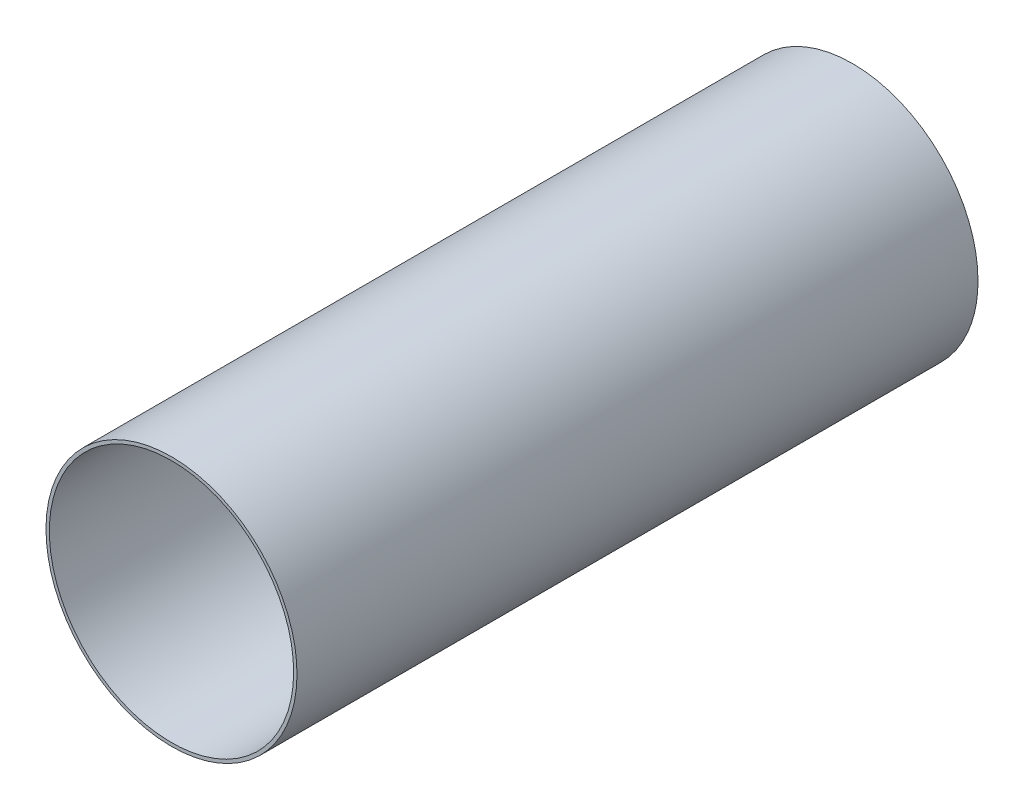
SolidWorks part; units mm, degrees
material "Thornel VCB-20 Carbon Cloth"
ref_plane "Piano frontale" through (0, 0, 0) normal (0, 0, 1) x (1, 0, 0)
ref_plane "Piano superiore" through (0, 0, 0) normal (0, 1, 0) x (1, 0, 0)
ref_plane "Piano destro" through (0, 0, 0) normal (1, 0, 0) x (0, 0, -1)
sketch "Schizzo1" plane through (0, 0, 0) normal (0, 0, 1) x (1, 0, 0)
  circle A0 centre (0, 0) radius 75
  dimension "D1" = 150
extrude "Estrusione-Sottile1" add sketch "Schizzo1" along normal up to surface (406.9685 mm away) thin thin type one direction reverse wall 2
ref_plane "Piano1" through (-75, 0, 0) normal (-1, 0, 0) x (0, 0, 1)
hole_wizard "Foro svasato per Vite M6-1" [suppressed] positions "Schizzo3" profile "Schizzo4" countersink size "M6" standard "ISO"
sketch "Schizzo3" plane through (-75, 0, 0) normal (-1, 0, 0) x (0, 0, 1)
  point P0 (19, 0)
  dimension "D1" = 19
sketch "Schizzo4" plane through (-75, 0, 15) normal (0, 1, 0) x (0, 0, 1)
  line L0 (0, 0) -> (0, 74.999)
  line L1 (0, 74.999) -> (3.3, 74.999)
  line L2 (3.3, 74.999) -> (3.3, 3)
  line L3 (3.3, 3) -> (6.3, 0)
  line L5 (6.3, 0) -> (0, 0)
  line L6 (-3.3, 3) -> (-6.3, 0) construction
  line L10 (0, 74.999) -> (-3.3, 74.999) construction
  line L11 (0, -6.35) -> (0, 107.95) construction
  dimension "Hole Dia." = 6.6
  dimension "Hole Depth" = 74.999
  dimension "Near C'Sink Dia." = 12.6
  dimension "Near C'Sink Angle" = 90
  dimension "Drill Angle" = 180
pattern_circular "RipetizioneCircolare1" [suppressed] count 10 over 360
sketch3d "Schizzo3D2"
  line L0 (-75, 0, 0) -> (-75, 0, 21)
  line L1 (0, 0, 0) -> (0, 0, 36.4754) construction
  circle A0 centre (0, 0, 0) radius 75 construction
  point P0 (-75, 0, 0)
  point P4 (0, 0, 75)
  dimension "D1" = 21
